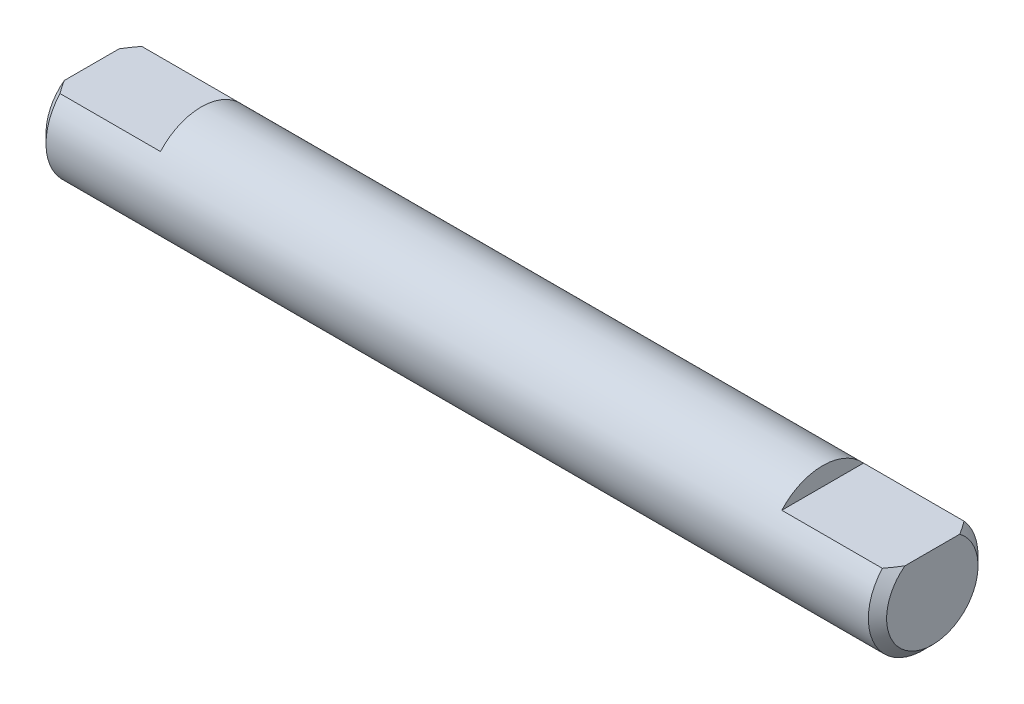
SolidWorks part; units mm, degrees
ref_plane "Front Plane" through (0, 0, 0) normal (0, 0, 1) x (1, 0, 0)
ref_plane "Top Plane" through (0, 0, 0) normal (0, 1, 0) x (1, 0, 0)
ref_plane "Right Plane" through (0, 0, 0) normal (1, 0, 0) x (0, 0, -1)
sketch "Sketch1" plane through (0, 0, 0) normal (1, 0, 0) x (0, 0, -1)
  circle A0 centre (0, 0) radius 3
  dimension "D1" = 6
extrude "Boss-Extrude1" add sketch "Sketch1" along normal mid plane 46
chamfer "Chamfer1" distance 0.5 angle 45 2 edges at (-23, 0, -3) (23, 0, -3)
sketch "Sketch2" plane through (23, 0, 0) normal (1, 0, 0) x (0, 0, -1)
  line L0 (-2.2361, 2) -> (2.2361, 2)
  arc A0 (2.2361, 2) -> (-2.2361, 2) centre (0, 0) ccw
  dimension "D1" = 2
extrude "Cut-Extrude1" cut sketch "Sketch2" against normal blind 6
mirror "Mirror1" about plane through (0, 0, 0) normal (1, 0, 0) of "Cut-Extrude1"
